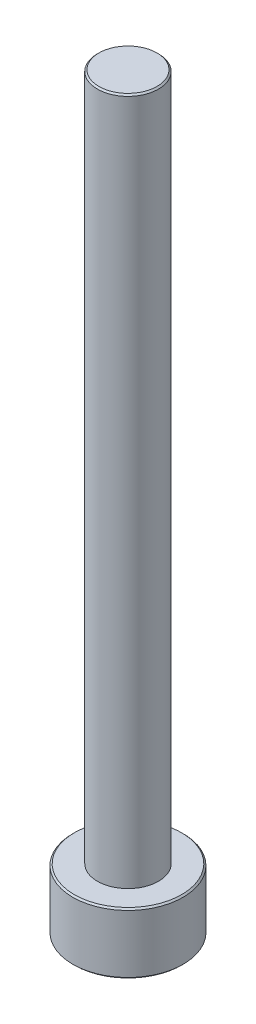
SolidWorks part; units mm, degrees
material "Q235"
ref_plane "前视基准面" through (0, 0, 0) normal (0, 0, 1) x (1, 0, 0)
ref_plane "上视基准面" through (0, 0, 0) normal (0, 1, 0) x (1, 0, 0)
ref_plane "右视基准面" through (0, 0, 0) normal (1, 0, 0) x (0, 0, -1)
sketch "草图1" plane through (0, 0, 0) normal (0, 1, 0) x (1, 0, 0)
  circle A0 centre (0, 0) radius 3.61
  dimension "D1" = 7.22
extrude "杯头部分" add sketch "草图1" along normal blind 4
sketch "草图2" plane through (0, 4, 0) normal (0, 1, 0) x (1, 0, 0)
  circle A0 centre (0, 0) radius 2
  dimension "D1" = 4
extrude "螺柱部分" add sketch "草图2" along normal blind 45
cosmetic thread "装饰螺纹线1" parameters "D2"=2.459
sketch "草图3" plane through (0, 0, 0) normal (0, -1, 0) x (1, 0, 0)
  line L1 (1.54, -0.8891) -> (1.54, 0.8891)
  line L2 (1.54, 0.8891) -> (0, 1.7782)
  line L3 (0, 1.7782) -> (-1.54, 0.8891)
  line L4 (-1.54, 0.8891) -> (-1.54, -0.8891)
  line L5 (-1.54, -0.8891) -> (0, -1.7782)
  line L6 (0, -1.7782) -> (1.54, -0.8891)
  circle A0 centre (0, 0) radius 1.54 construction
  dimension "D1" = 3.08
extrude "沉头内六角" cut sketch "草图3" against normal blind 2
chamfer "修饰性倒角" distance 0.1 angle 45 3 edges at (0, 49, 2) (0, 4, 3.61) (0, 0, 3.61)
